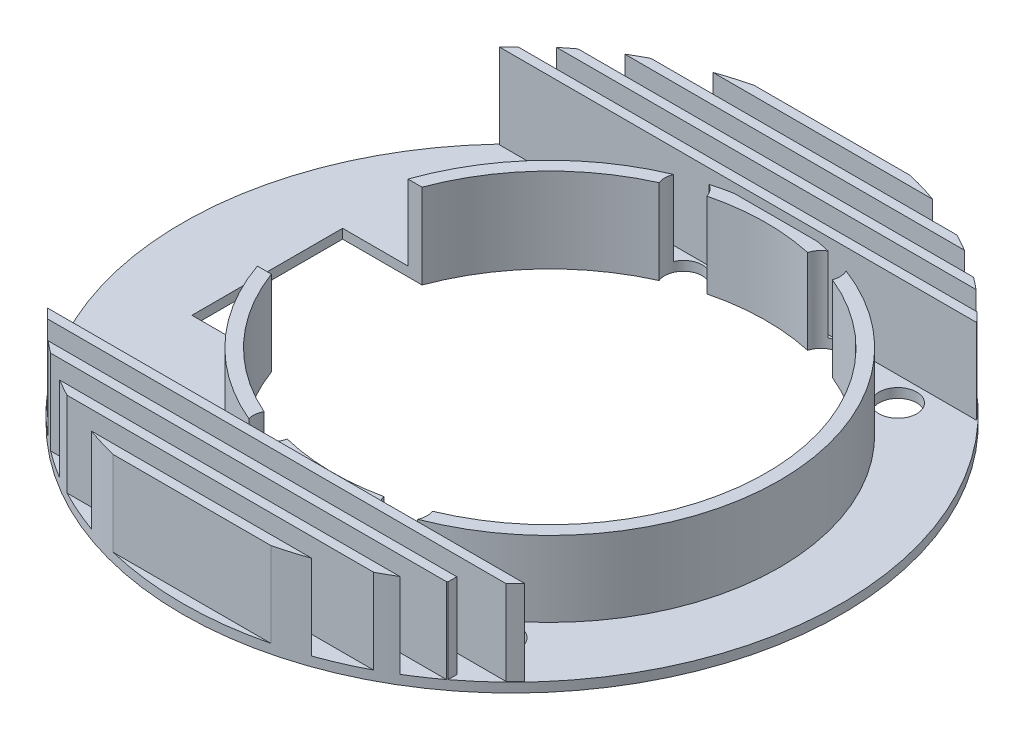
SolidWorks part; units mm, degrees
ref_plane "Front Plane" through (0, 0, 0) normal (0, 0, 1) x (1, 0, 0)
ref_plane "Top Plane" through (0, 0, 0) normal (0, 1, 0) x (1, 0, 0)
ref_plane "Right Plane" through (0, 0, 0) normal (1, 0, 0) x (0, 0, -1)
sketch "Sketch1" plane through (0, 0, 0) normal (0, 1, 0) x (1, 0, 0)
  circle A0 centre (0, 0) radius 17.5
extrude "Boss-Extrude1" add sketch "Sketch1" along normal blind 0.5
sketch "Sketch2" plane through (0, 0.5, 0) normal (0, 1, 0) x (1, 0, 0)
  circle A0 centre (2, 0) radius 11.5
extrude "Cut-Extrude1" cut sketch "Sketch2" against normal blind 0.5
sketch "Sketch3" plane through (0, 0, 0) normal (0, 1, 0) x (1, 0, 0)
  line L1 (2, 4) -> (-13, 4)
  line L2 (2, 4) -> (2, -4)
  line L3 (2, -4) -> (-13, -4)
  line L4 (-13, 4) -> (-13, -4)
extrude "Cut-Extrude4" cut sketch "Sketch3" along normal blind 2.5
sketch "Sketch4" plane through (0, 0, 0) normal (0, 1, 0) x (1, 0, 0)
  circle A0 centre (0, 0) radius 17.2585
  circle A1 centre (0, 0) radius 15.5
sketch "Sketch5" plane through (0, 0.5, 0) normal (0, 1, 0) x (1, 0, 0)
  circle A0 centre (0, 0) radius 14.5
  circle A1 centre (0, 0) radius 14.5
  circle A2 centre (0, 0) radius 14
sketch "Sketch6" plane through (0, 0.5, 0) normal (0, 1, 0) x (1, 0, 0)
  circle A0 centre (0, 0) radius 17.5
  circle A1 centre (0, 0) radius 17
sketch "Sketch7" plane through (0, 0.5, 0) normal (0, 1, 0) x (1, 0, 0)
  line L0 (0, 12.5) -> (0, 13.5)
  line L1 (0, 14) -> (0, 15)
  line L2 (0, 12) -> (12.6696, 12)
  line L3 (12.6696, 12) -> (0, 12)
  line L4 (-12.6696, 12) -> (0, 12)
  line L5 (0, -12) -> (12.6696, -12)
  line L6 (12.6696, -12) -> (0, -12)
  line L7 (0, -12) -> (-12.6696, -12)
  line L8 (0, 12.5) -> (-12.1765, 12.5)
  line L9 (0, -12.5) -> (-12.1765, -12.5)
  line L10 (0, -12.5) -> (12.1765, -12.5)
  line L11 (0, 12.5) -> (12.1765, 12.5)
  line L12 (-15.0094, 14) -> (0, 14)
  line L13 (-15.0094, 14) -> (-15.0094, 13.5)
  line L14 (-15.0094, 13.5) -> (0, 13.5)
  line L15 (0, 14) -> (0, 13.5)
  line L16 (12.6696, 13.5) -> (0, 13.5)
  line L17 (12.6696, 13.5) -> (12.6696, 14)
  line L18 (12.6696, 14) -> (0, 14)
  line L19 (0, 13.5) -> (0, 14)
  line L20 (0, 15.5) -> (0, 16.5)
  line L21 (0, 15) -> (-12.1765, 15)
  line L22 (0, 15) -> (0, 15.5)
  line L23 (0, 15.5) -> (-12.1765, 15.5)
  line L24 (-12.1765, 15) -> (-12.1765, 15.5)
  line L25 (10.5562, 15) -> (0, 15)
  line L26 (10.5562, 15) -> (10.5562, 15.5)
  line L27 (10.5562, 15.5) -> (0, 15.5)
  line L28 (0, 15) -> (0, 15.5)
  line L30 (0, 16.5) -> (-8.985, 16.5)
  line L31 (0, 16.5) -> (0, 17)
  line L32 (0, 17) -> (-8.985, 17)
  line L33 (-8.985, 16.5) -> (-8.985, 17)
  line L34 (9.7018, 17) -> (0, 17)
  line L35 (9.7018, 17) -> (9.7018, 16.5)
  line L36 (9.7018, 16.5) -> (0, 16.5)
  line L37 (0, 17) -> (0, 16.5)
  line L39 (-0.0002, -16.992) -> (12.6693, -16.992)
  line L40 (12.6693, -16.992) -> (-0.0002, -16.992)
  line L41 (-12.6698, -16.992) -> (-0.0002, -16.992)
  line L42 (-0.0002, -16.492) -> (-12.1768, -16.492)
  line L43 (-0.0002, -16.492) -> (12.1763, -16.492)
  line L44 (-15.0096, -14.992) -> (-0.0002, -14.992)
  line L45 (-15.0096, -14.992) -> (-15.0096, -15.492)
  line L46 (-15.0096, -15.492) -> (-0.0002, -15.492)
  line L47 (-0.0002, -14.992) -> (-0.0002, -15.492)
  line L48 (12.6693, -15.492) -> (-0.0002, -15.492)
  line L49 (12.6693, -15.492) -> (12.6693, -14.992)
  line L50 (12.6693, -14.992) -> (-0.0002, -14.992)
  line L51 (-0.0002, -15.492) -> (-0.0002, -14.992)
  line L53 (-0.0002, -13.992) -> (-12.1768, -13.992)
  line L54 (-0.0002, -13.992) -> (-0.0002, -13.492)
  line L55 (-0.0002, -13.492) -> (-12.1768, -13.492)
  line L56 (-12.1768, -13.992) -> (-12.1768, -13.492)
  line L57 (10.556, -13.992) -> (-0.0002, -13.992)
  line L58 (10.556, -13.992) -> (10.556, -13.492)
  line L59 (10.556, -13.492) -> (-0.0002, -13.492)
  line L60 (-0.0002, -13.992) -> (-0.0002, -13.492)
  arc A0 (12.1765, -12.5) -> (12.6696, -12) centre (0, 0) ccw
  arc A1 (12.1765, 12.5) -> (12.6696, 12) centre (0, 0) cw
  arc A2 (-12.1765, -12.5) -> (-12.6696, -12) centre (0, 0) cw
  arc A3 (-12.1765, 12.5) -> (-12.6696, 12) centre (0, 0) ccw
  arc A4 (12.1763, -16.492) -> (12.6693, -16.992) centre (-0.0002, -28.992) cw
  arc A5 (-12.1768, -16.492) -> (-12.6698, -16.992) centre (-0.0002, -28.992) ccw
  circle M10 centre (0, 0) radius 17.5
extrude "Boss-Extrude6" add sketch "Sketch7" along normal blind 4.5 contours A2 L9 L10 A0 L5 L7 | L54 L55 L53 M10 | L58 L59 L54 L57 M10 | L47 L44 L46 M10 | L50 L47 L48 M10 | L43 L42 L41 L39 M10 | L22 L23 L21 M10 | L27 L22 L25 M10 | L15 L12 L14 M10 | L18 L15 L16 M10 | L8 A3 L4 L2 A1 L11 | L31 L32 L30 M10 | L36 L34 L31 M10
sketch "Sketch9" plane through (0, 0.5, 0) normal (0, 1, 0) x (1, 0, 0)
  circle A0 centre (2, 0) radius 12.2
  circle A1 centre (2, 0) radius 11.5
extrude "Boss-Extrude7" add sketch "Sketch9" along normal blind 4
sketch "Sketch10" plane through (0, 0, 0) normal (0, -1, 0) x (1, 0, 0)
  line L1 (-13, -4) -> (-8.7819, -4)
  line L2 (-13, -4) -> (-13, 4)
  line L3 (-13, 4) -> (-8.7819, 4)
  line L4 (-8.7819, -4) -> (-8.7819, 4)
extrude "Cut-Extrude5" cut sketch "Sketch10" against normal blind 6
sketch "Sketch11" plane through (0, 0, 0) normal (0, -1, 0) x (1, 0, 0)
  line L1 (10.0136, -23.0635) -> (5.4296, -23.0635)
  line L3 (5.4296, 24.381) -> (1.1894, 24.381)
  line L7 (-3.0508, 24.381) -> (-6.9472, 24.381)
  circle A0 centre (-117577.4605, -236651.4879) radius 0.0006
  arc A1 (-8.7819, -4) -> (-8.7819, 4) centre (2, 0) ccw construction
  circle A2 centre (-7.3403, -10.1425) radius 1
  circle A3 centre (-1.7676, -10.8653) radius 0.9987
  circle A4 centre (5.4296, -10.9767) radius 0.9987
  circle A6 centre (-7.3403, 9.9174) radius 1
  circle A7 centre (5.4296, 10.9767) radius 1.0326
  circle A8 centre (-1.7676, 10.9767) radius 1
  circle A9 centre (10.0136, 10.6438) radius 1.0081
  circle A10 centre (9.7724, -10.7122) radius 1
  circle A11 centre (0, 0) radius 14.5 construction
extrude "Cut-Extrude7" cut sketch "Sketch11" against normal blind 100 contours A2 | A3 | A4 | A10 | A9 | A7 | A8 | A6
